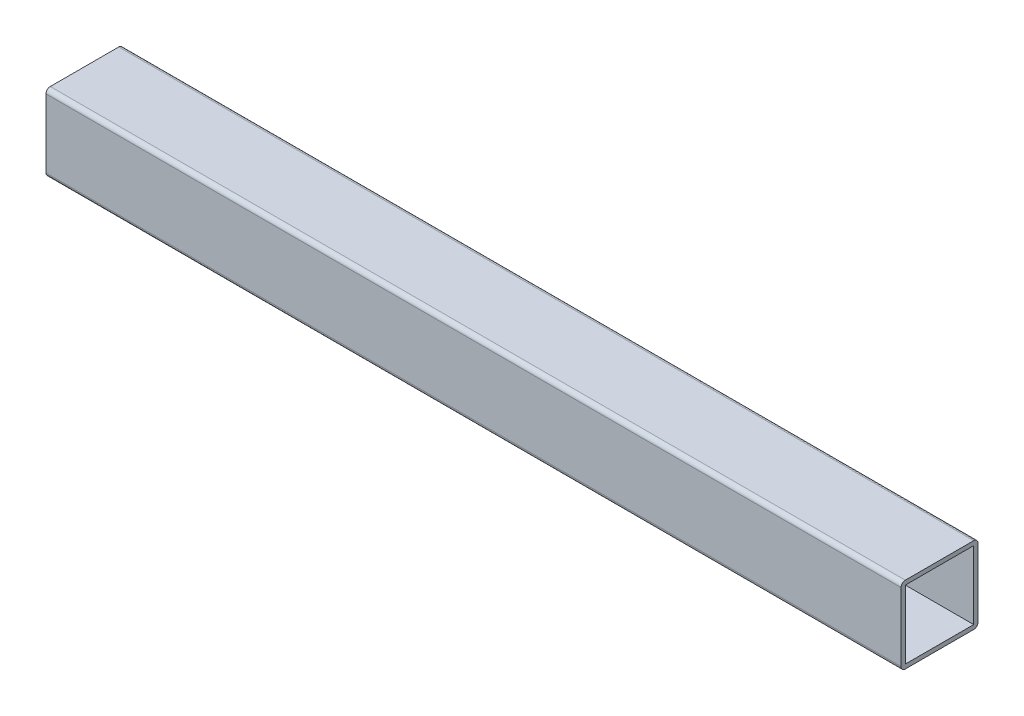
SolidWorks part; units mm, degrees
ref_plane "Front Plane" through (0, 0, 0) normal (0, 0, 1) x (1, 0, 0)
ref_plane "Top Plane" through (0, 0, 0) normal (0, 1, 0) x (1, 0, 0)
ref_plane "Right Plane" through (0, 0, 0) normal (1, 0, 0) x (0, 0, -1)
sketch "Sketch1" plane through (0, 0, 0) normal (1, 0, 0) x (0, 0, -1)
  line L0 (10, 10) -> (10, 170)
  line L1 (10, 0) -> (170, 0)
  line L2 (0, 10) -> (0, 170)
  line L3 (10, 180) -> (170, 180)
  line L4 (180, 10) -> (180, 170)
  line L5 (10, 10) -> (170, 10)
  line L6 (170, 10) -> (170, 170)
  line L7 (10, 170) -> (170, 170)
  arc A0 (0, 170) -> (10, 180) centre (10, 170) cw
  arc A1 (180, 170) -> (170, 180) centre (170, 170) ccw
  arc A2 (10, 0) -> (0, 10) centre (10, 10) cw
  arc A3 (170, 0) -> (180, 10) centre (170, 10) ccw
  point P6 (0, 180)
  point P9 (180, 180)
  point P12 (0, 0)
  dimension "D3" = 10
  dimension "Width" = 180
  dimension "D2" = 180
extrude "Extrude1" add sketch "Sketch1" along normal blind 2000
